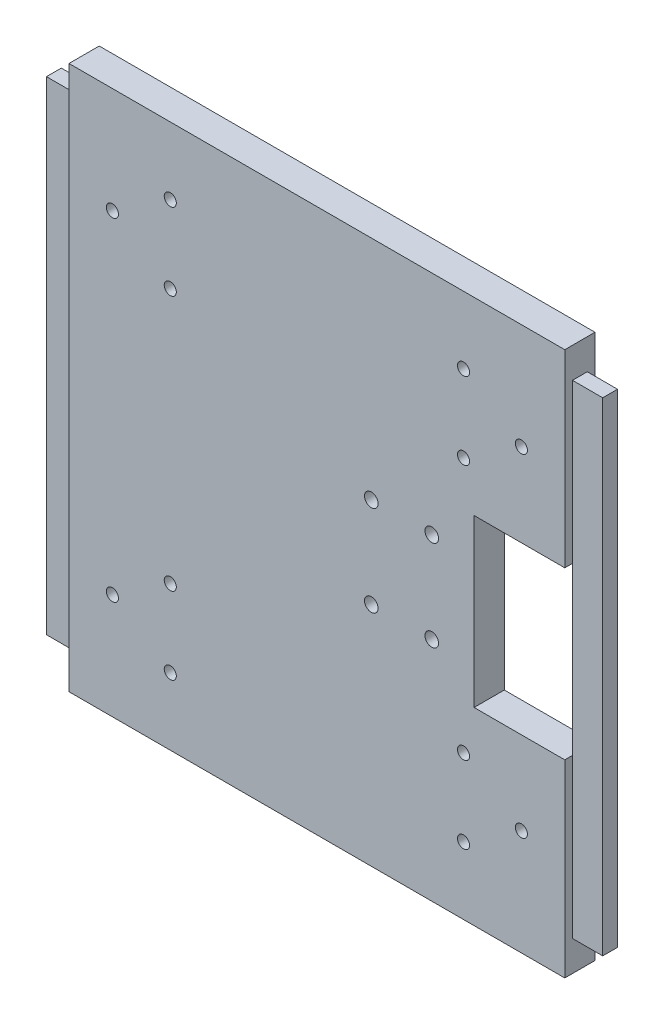
SolidWorks part; units mm, degrees
ref_plane "前视基准面" through (0, 0, 0) normal (0, 0, 1) x (1, 0, 0)
ref_plane "上视基准面" through (0, 0, 0) normal (0, 1, 0) x (1, 0, 0)
ref_plane "右视基准面" through (0, 0, 0) normal (1, 0, 0) x (0, 0, -1)
other "Configuration Table"
sketch "草图1" plane through (0, 0, 0) normal (0, 0, 1) x (1, 0, 0)
  line L1 (0, 0) -> (164, 0)
  line L2 (0, 0) -> (0, 180)
  line L3 (0, 180) -> (164, 180)
  line L4 (164, 0) -> (164, 180)
  line L5 (0, 0) -> (164, 180) construction
  line L6 (0, 180) -> (164, 0) construction
  point P4 (82, 90)
  dimension "D1" = 164
  dimension "D2" = 180
extrude "凸台-拉伸1" add sketch "草图1" along normal blind 10
sketch "草图2" plane through (0, 0, 0) normal (-1, 0, 0) x (0, 0, 1)
  line L0 (10, 180) -> (10, 0) construction
  line L1 (2.55, 169.95) -> (7.45, 169.95)
  line L2 (2.55, 169.95) -> (2.55, 10.05)
  line L3 (2.55, 10.05) -> (7.45, 10.05)
  line L4 (7.45, 169.95) -> (7.45, 10.05)
  line L5 (2.55, 169.95) -> (7.45, 10.05) construction
  line L6 (2.55, 10.05) -> (7.45, 169.95) construction
  line L7 (10, 180) -> (0, 180) construction
  point P4 (5, 90)
  dimension "D1" = 4.9
  dimension "D2" = 159.9
  dimension "D3" = 5
  dimension "D4" = 90
extrude "凸台-拉伸2" add sketch "草图2" along normal blind 10
ref_plane "基准面1" through (82, 0, 0) normal (1, 0, 0) x (0, 0, -1)
mirror "镜向1" about plane through (82, 0, 0) normal (1, 0, 0) of "凸台-拉伸2"
sketch "草图3" plane through (0, 0, 0) normal (0, 0, -1) x (-1, 0, 0)
  line L0 (-164, 169.95) -> (-164, 10.05) construction
  line L1 (-164, 90) -> (12.5762, 90) construction
  line L2 (-174, 169.95) -> (-174, 10.05) construction
  line L3 (-164, 0) -> (-164, 180) construction
  line L4 (0, 169.95) -> (0, 10.05) construction
  line L5 (0, 180) -> (0, 0) construction
  circle A0 centre (-149.6426, 145) radius 2
  circle A1 centre (-130.5, 157.75) radius 2
  circle A2 centre (-130.5, 132.25) radius 2
  circle A3 centre (-14.3574, 145) radius 2
  circle A4 centre (-33.5, 157.75) radius 2
  circle A5 centre (-33.5, 132.25) radius 2
  circle A6 centre (-130.5, 47.75) radius 2
  circle A7 centre (-130.5, 22.25) radius 2
  circle A8 centre (-149.6426, 35) radius 2
  circle A9 centre (-33.5, 47.75) radius 2
  circle A10 centre (-33.5, 22.25) radius 2
  circle A11 centre (-14.3574, 35) radius 2
  dimension "D1" = 4
  dimension "D2" = 4
  dimension "D3" = 4
  dimension "D4" = 4
  dimension "D5" = 4
  dimension "D6" = 4
  dimension "D7" = 23
  dimension "D8" = 23
  dimension "D9" = 25.5
  dimension "D10" = 10
  dimension "D11" = 55
  dimension "D12" = 33.5
  dimension "D13" = 25.5
  dimension "D14" = 23
  dimension "D15" = 23
  dimension "D16" = 33.5
  dimension "D17" = 33.5
  dimension "D18" = 55
  dimension "D19" = 33.5
extrude "切除-拉伸1" cut sketch "草图3" against normal blind 10
sketch "草图5" plane through (0, 0, 10) normal (0, 0, 1) x (1, 0, 0)
  line L0 (0, 90) -> (164, 90) construction
  line L1 (85.1179, 105) -> (85.1179, 75) construction
  line L3 (0, 10.05) -> (0, 169.95) construction
  line L4 (5, 110.5) -> (125, 110.5) construction
  line L5 (5, 110.5) -> (5, 69.5) construction
  line L6 (5, 69.5) -> (125, 69.5) construction
  line L7 (125, 110.5) -> (125, 69.5) construction
  line L8 (5, 110.5) -> (125, 69.5) construction
  line L9 (5, 69.5) -> (125, 110.5) construction
  line L10 (119.1179, 117.5) -> (156.1179, 117.5)
  line L11 (75.1179, 110) -> (118.1179, 110) construction
  line L12 (75.1179, 110) -> (75.1179, 70) construction
  line L13 (75.1179, 70) -> (118.1179, 70) construction
  line L14 (118.1179, 110) -> (118.1179, 70) construction
  line L15 (75.1179, 110) -> (118.1179, 70) construction
  line L16 (75.1179, 70) -> (118.1179, 110) construction
  line L17 (119.1179, 117.5) -> (119.1179, 62.5)
  line L18 (119.1179, 62.5) -> (156.1179, 62.5)
  line L19 (156.1179, 117.5) -> (156.1179, 62.5)
  line L20 (119.1179, 117.5) -> (156.1179, 62.5) construction
  line L21 (119.1179, 62.5) -> (156.1179, 117.5) construction
  circle A1 centre (85.1179, 105) radius 2.5
  circle A2 centre (85.1179, 75) radius 2.5
  circle A5 centre (105.1179, 105) radius 2.5
  circle A6 centre (105.1179, 75) radius 2.5
  point P5 (65, 90)
  point P13 (96.6179, 90)
  point P22 (85.1179, 90)
  point P27 (137.6179, 90)
  dimension "D5" = 43
  dimension "D7" = 5
  dimension "D8" = 2
  dimension "D9" = 5
  dimension "D10" = 55
  dimension "D1" = 120
  dimension "D2" = 41
  dimension "D3" = 5
  dimension "D4" = 6.8821
  dimension "D6" = 40
  dimension "D11" = 30
  dimension "D12" = 10
  dimension "D13" = 37
  dimension "D14" = 2
extrude "切除-拉伸3" [suppressed] cut sketch "草图5" against normal blind 8
sketch "草图6" [suppressed] plane through (0, 0, 2) normal (0, 0, 1) x (1, 0, 0)
  line L4 (119.1179, 117.5) -> (119.1179, 62.5)
  line L5 (119.1179, 62.5) -> (156.1179, 62.5)
  line L6 (156.1179, 62.5) -> (156.1179, 117.5)
  line L7 (156.1179, 117.5) -> (119.1179, 117.5)
  line L8 (119.1179, 117.5) -> (119.1179, 62.5)
  line L9 (119.1179, 62.5) -> (156.1179, 62.5)
  line L10 (156.1179, 62.5) -> (156.1179, 117.5)
  line L11 (156.1179, 117.5) -> (119.1179, 117.5)
  dimension "D1" = 0
extrude "切除-拉伸4" [suppressed] cut sketch "草图6" against normal blind 8
ref_plane "基准面2" through (0, 0, 10) normal (0, 0, 1) x (1, 0, 0)
sketch "草图7" plane through (0, 0, 10) normal (0, 0, 1) x (1, 0, 0)
  line L1 (134, 117.5) -> (164, 117.5)
  line L2 (134, 117.5) -> (134, 62.5)
  line L3 (134, 62.5) -> (164, 62.5)
  line L4 (156.1179, 117.5) -> (119.1179, 117.5)
  line L5 (156.1179, 62.5) -> (156.1179, 117.5)
  line L6 (119.1179, 62.5) -> (156.1179, 62.5)
  line L7 (119.1179, 117.5) -> (119.1179, 62.5)
  line L8 (156.1179, 117.5) -> (119.1179, 117.5) construction
  line L9 (156.1179, 62.5) -> (156.1179, 117.5) construction
  line L10 (119.1179, 62.5) -> (156.1179, 62.5) construction
  line L11 (119.1179, 117.5) -> (119.1179, 62.5) construction
  line L12 (164, 117.5) -> (164, 62.5)
  line L13 (134, 117.5) -> (164, 62.5) construction
  line L14 (134, 62.5) -> (164, 117.5) construction
  line L16 (164, 0) -> (164, 180) construction
  line L17 (164, 0) -> (164, 180)
  circle A0 centre (120, 105) radius 2.25
  circle A1 centre (105.1179, 75) radius 2.5
  circle A2 centre (105.1179, 75) radius 2.5 construction
  circle A3 centre (105.1179, 105) radius 2.5
  circle A4 centre (105.1179, 105) radius 2.5 construction
  circle A5 centre (85.1179, 75) radius 2.5
  circle A6 centre (85.1179, 75) radius 2.5 construction
  circle A7 centre (85.1179, 105) radius 2.5
  circle A8 centre (85.1179, 105) radius 2.5 construction
  circle A9 centre (120, 75) radius 2.25
  circle A10 centre (100, 105) radius 2.25
  circle A11 centre (100, 75) radius 2.25
  point P20 (149, 90)
  dimension "D10" = 4.5
  dimension "D11" = 4.5
  dimension "D6" = 30
  dimension "D7" = 0
  dimension "D8" = 14
  dimension "D9" = 14
  dimension "D12" = 2
  dimension "D1" = 0
  dimension "D2" = 0
  dimension "D3" = 0
  dimension "D4" = 0
  dimension "D5" = 0
extrude "切除-拉伸5" cut sketch "草图7" against normal through all contours L1 L12 L3 L2 | A0 | A10 | A11 | A9
